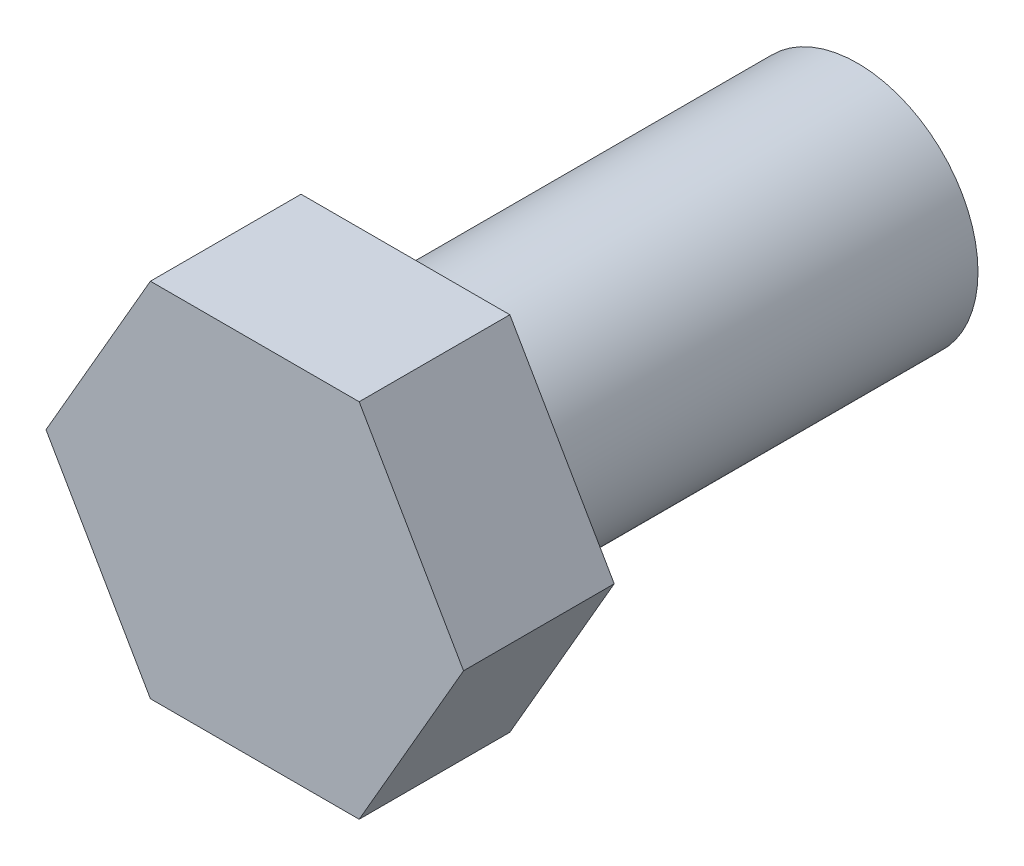
SolidWorks part; units mm, degrees
material "AISI 304"
ref_plane "Front Plane" through (0, 0, 0) normal (0, 0, 1) x (1, 0, 0)
ref_plane "Top Plane" through (0, 0, 0) normal (0, 1, 0) x (1, 0, 0)
ref_plane "Right Plane" through (0, 0, 0) normal (1, 0, 0) x (0, 0, -1)
sketch "Sketch1" plane through (0, 0, 0) normal (0, 0, 1) x (1, 0, 0)
  circle A0 centre (0, 0) radius 8
  dimension "D1" = 16
extrude "Extrude1" add sketch "Sketch1" against normal blind 30
cosmetic thread "Cosmetic Thread1" parameters "D1"=30, "D2"=6.5278
sketch "Sketch2" plane through (0, 0, 0) normal (0, 0, 1) x (1, 0, 0)
  line L1 (-6.9282, 12) -> (-13.8564, 0)
  line L2 (-13.8564, 0) -> (-6.9282, -12)
  line L3 (-6.9282, -12) -> (6.9282, -12)
  line L4 (6.9282, -12) -> (13.8564, 0)
  line L5 (13.8564, 0) -> (6.9282, 12)
  line L6 (6.9282, 12) -> (-6.9282, 12)
  circle A0 centre (0, 0) radius 12 construction
  dimension "D1" = 24
extrude "Extrude2" add sketch "Sketch2" along normal blind 10
